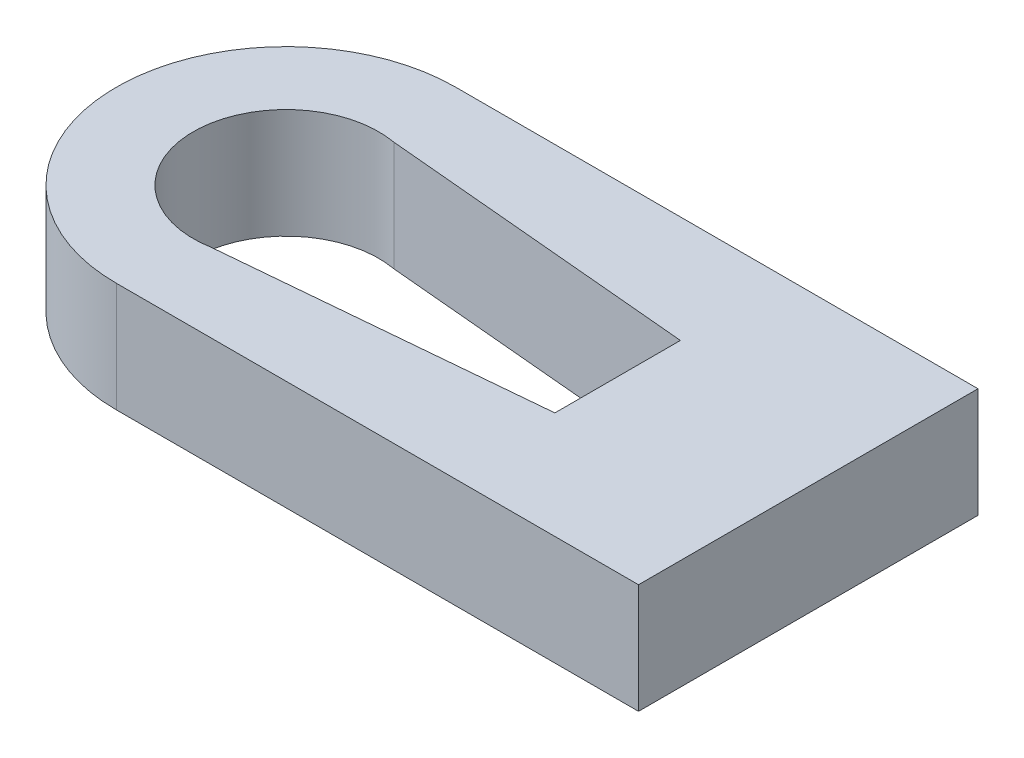
SolidWorks part; units mm, degrees
material "ABS"
ref_plane "Front Plane" through (0, 0, 0) normal (0, 0, 1) x (1, 0, 0)
ref_plane "Top Plane" through (0, 0, 0) normal (0, 1, 0) x (1, 0, 0)
ref_plane "Right Plane" through (0, 0, 0) normal (1, 0, 0) x (0, 0, -1)
sketch "Sketch1" plane through (0, 0, 0) normal (0, 1, 0) x (1, 0, 0)
  circle A0 centre (0, 0) radius 6.5
extrude "Boss-Extrude1" add sketch "Sketch1" along normal mid plane 4.2 from offset 21.4
sketch "Sketch2" plane through (0, 0, 0) normal (0, 1, 0) x (1, 0, 0)
  line L1 (0, -6.5) -> (20, -6.5)
  line L2 (0, -6.5) -> (0, 6.5)
  line L3 (0, 6.5) -> (20, 6.5)
  line L4 (20, -6.5) -> (20, 6.5)
  circle A0 centre (0, 0) radius 6.5 construction
extrude "Boss-Extrude2" add sketch "Sketch2" along normal mid plane 4.2 from offset 21.4
sketch "Sketch3" plane through (0, 0, 0) normal (0, 1, 0) x (1, 0, 0)
  circle A0 centre (0, 0) radius 3.55
extrude "Cut-Extrude1" cut sketch "Sketch3" against normal mid plane 4.2 from offset 21.4
sketch "Sketch4" plane through (0, 0, 0) normal (0, 1, 0) x (1, 0, 0)
  line L0 (0, -3.55) -> (12.7, -2.4033)
  line L1 (12.7, -2.4033) -> (12.7, 2.4033)
  line L2 (12.7, 2.4033) -> (0, 3.55)
  line L3 (0, 3.55) -> (0, -3.55)
  circle A0 centre (0, 0) radius 3.55 construction
extrude "Cut-Extrude2" cut sketch "Sketch4" against normal mid plane 4.2 from offset 21.4
